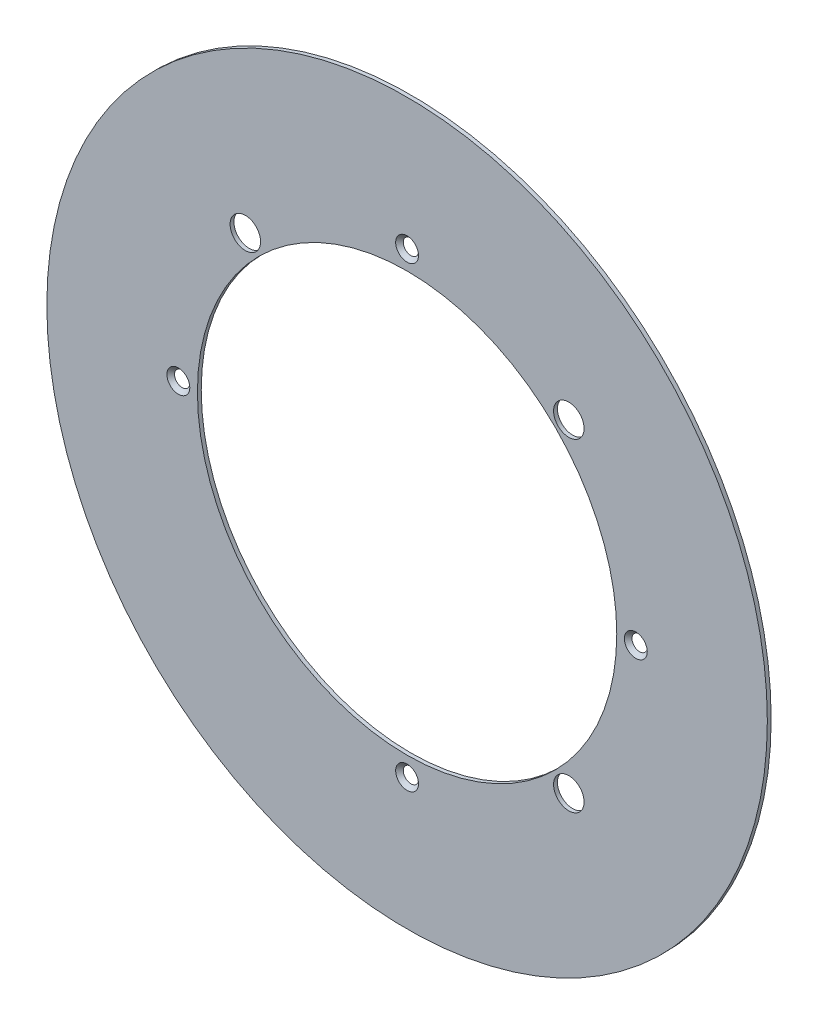
SolidWorks part; units mm, degrees
material "Alliage 6061"
ref_plane "Face" through (0, 0, 0) normal (0, 0, 1) x (1, 0, 0)
ref_plane "Dessus" through (0, 0, 0) normal (0, 1, 0) x (1, 0, 0)
ref_plane "Droite" through (0, 0, 0) normal (1, 0, 0) x (0, 0, -1)
sketch "Esquisse1" plane through (0, 0, 0) normal (0, 0, 1) x (1, 0, 0)
  circle A0 centre (0, 0) radius 94.5
  circle A1 centre (0, 0) radius 55
  dimension "D1" = 189
  dimension "D2" = 110
extrude "Boss.-Extru.1" add sketch "Esquisse1" along normal blind 1
sketch "Esquisse2" plane through (0, 0, 1) normal (0, 0, 1) x (1, 0, 0)
  line L0 (0, 60) -> (0, -60) construction
  line L1 (-60, 0) -> (60, 0) construction
  line L2 (-42.4264, 42.4264) -> (42.4264, -42.4264) construction
  line L3 (42.4264, 42.4264) -> (-42.4264, -42.4264) construction
  circle A0 centre (0, 0) radius 60 construction
  circle A1 centre (42.4264, 42.4264) radius 4
  circle A2 centre (-42.4264, 42.4264) radius 4
  circle A3 centre (42.4264, -42.4264) radius 4
  dimension "D1" = 120
  dimension "D2" = 45
  dimension "D3" = 45
extrude "Enlèv. mat.-Extru.2" cut sketch "Esquisse2" against normal up to next
hole_wizard "Fraisage pour vis à tête fraisée M31" positions "Esquisse4" profile "Esquisse3" countersink size "M3" standard "Din" end condition up to next
sketch "Esquisse4" plane through (0, 0, 1) normal (0, 0, 1) x (1, 0, 0)
  point P0 (0, 60)
  point P3 (60, 0)
  point P6 (0, -60)
  point P9 (-60, 0)
sketch "Esquisse3" plane through (0, 60, 1) normal (1, 0, 0) x (0, -1, 0)
  line L0 (0, 0) -> (0, 1)
  line L1 (0, 1) -> (1.6, 1)
  line L2 (1.6, 1) -> (1.6, 1.4)
  line L3 (1.6, 1.4) -> (3, 0)
  line L5 (3, 0) -> (0, 0)
  line L6 (-1.6, 1.4) -> (-3, 0) construction
  line L11 (0, -6.35) -> (0, 107.95) construction
  dimension "Diamètre du perçage jusqu'au prochain" = 3.2
  dimension "Profondeur du perçage jusqu'au prochain" = 1
  dimension "Diamètre du fraisage entrant" = 6
  dimension "Angle du fraisage entrant" = 90
